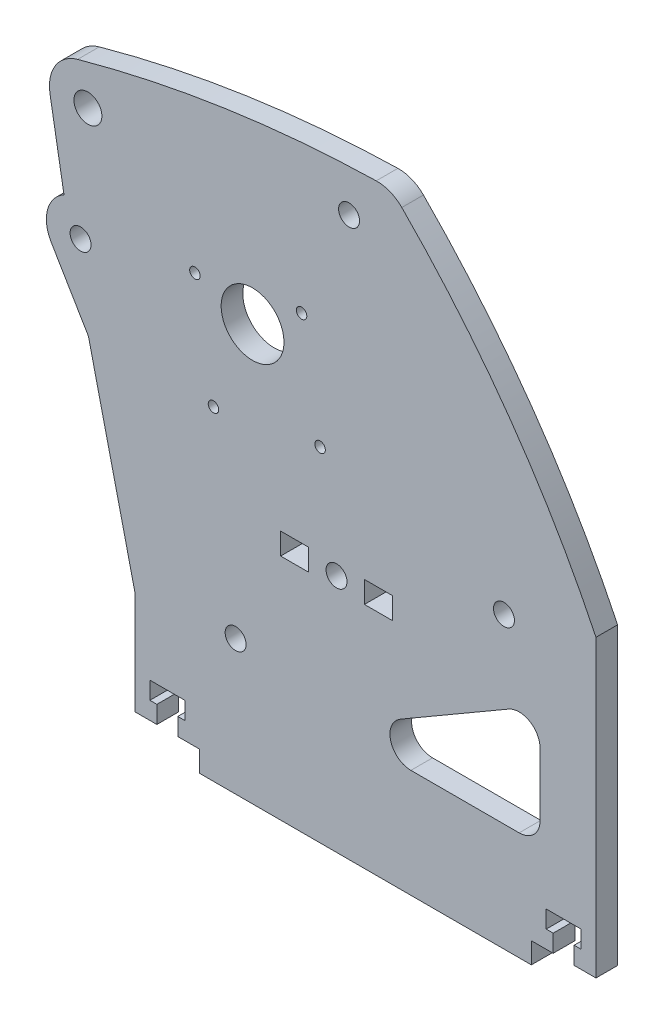
SolidWorks part; units mm, degrees
ref_plane "Front Plane" through (0, 0, 0) normal (0, 0, 1) x (1, 0, 0)
ref_plane "Top Plane" through (0, 0, 0) normal (0, 1, 0) x (1, 0, 0)
ref_plane "Right Plane" through (0, 0, 0) normal (1, 0, 0) x (0, 0, -1)
sketch "Sketch1" plane through (0, 0, 0) normal (0, 0, 1) x (1, 0, 0)
  line L5 (-57.6783, -8.5) -> (-47, -26.5)
  line L7 (-33.65, -83.5) -> (-33.65, -113)
  line L8 (-33.65, -113) -> (-15.15, -113)
  line L12 (82.35, -64) -> (82.35, -82)
  line L13 (76.35, -88) -> (45.35, -88)
  line L14 (42.3372, -76.8113) -> (73.3372, -58.8113)
  line L15 (98.35, -28.5) -> (98.35, -113)
  line L16 (-47, -26.5) -> (-33.65, -83.5)
  line L17 (-58, 28.0717) -> (-54, 5.0717)
  line L18 (-15.15, -113) -> (-15.15, -119)
  line L19 (-15.15, -119) -> (79.85, -119)
  line L20 (79.85, -119) -> (79.85, -113)
  line L21 (79.85, -113) -> (98.35, -113)
  circle A0 centre (-47.15, 30) radius 4
  circle A1 centre (0, 0) radius 18.05 construction
  circle A2 centre (27.65, 40.9) radius 3
  circle A3 centre (-4.85, -80.4) radius 3
  circle A4 centre (-49.25, -3.5) radius 3
  circle A5 centre (72, -36) radius 3
  circle A6 centre (0, 0) radius 9
  arc A7 (-50.0938, 40.6196) -> (-58, 28.0717) centre (-47.15, 30) ccw
  arc A8 (-54, 5.0717) -> (-57.6783, -8.5) centre (-49.25, -3.5) ccw
  arc A10 (98.35, -28.5) -> (42.7481, 50.2939) centre (-163.098, -153.9789) ccw
  arc A11 (42.7481, 50.2939) -> (35.422, 53.2474) centre (35.65, 43.25) ccw
  arc A13 (82.35, -64) -> (73.3372, -58.8113) centre (76.35, -64) ccw
  arc A14 (76.35, -88) -> (82.35, -82) centre (76.35, -82) ccw
  arc A15 (42.3372, -76.8113) -> (45.35, -88) centre (45.35, -82) ccw
  arc A16 (-50.0938, 40.6196) -> (35.422, 53.2474) centre (43.4017, -296.6616) cw
  dimension "D1" = 18
  dimension "D3" = 40.9
  dimension "D4" = 6
  dimension "D5" = 47.15
  dimension "D6" = 30
  dimension "D7" = 8
  dimension "D8" = 72
  dimension "D10" = 49.25
  dimension "D11" = 3.5
  dimension "D12" = 80.4
  dimension "D13" = 4.85
  dimension "D25" = 350
  dimension "D26" = 10
  dimension "D29" = 290
  dimension "D34" = 6
  dimension "D2" = 27.65
  dimension "D9" = 36
  dimension "D14" = 113
  dimension "D15" = 132
  dimension "D16" = 33.65
  dimension "D17" = 83.5
  dimension "D18" = 47
  dimension "D19" = 57
  dimension "D20" = 84.5
  dimension "D21" = 18
  dimension "D22" = 54
  dimension "D23" = 23
  dimension "D24" = 58
  dimension "D27" = 2.35
  dimension "D28" = 8
  dimension "D30" = 31
  dimension "D31" = 18
  dimension "D32" = 16
  dimension "D33" = 25
  dimension "D35" = 95
  dimension "D36" = 6
  dimension "D37" = 18.5
extrude "Boss-Extrude1" add sketch "Sketch1" along normal blind 6.2
sketch "Sketch2" plane through (0, 0, 6.2) normal (0, 0, 1) x (1, 0, 0)
  circle A0 centre (19.3487, -20.7923) radius 1.5 construction
  circle A1 centre (-11.1929, -26.1038) radius 1.5 construction
  circle A2 centre (-16.5044, 4.4377) radius 1.5 construction
  circle A3 centre (14.0371, 9.7493) radius 1.5 construction
  circle A4 centre (19.3487, -20.7923) radius 1.5
  circle A5 centre (-11.1929, -26.1038) radius 1.5
  circle A6 centre (-16.5044, 4.4377) radius 1.5
  circle A7 centre (14.0371, 9.7493) radius 1.5
extrude "Cut-Extrude1" cut sketch "Sketch2" against normal up to next
ref_plane "Plane1" through (32.35, 0, 0) normal (1, 0, 0) x (0, 0, -1)
sketch "Sketch3" plane through (0, 0, 6.2) normal (0, 0, 1) x (1, 0, 0)
  line L0 (-33.65, -113) -> (-15.15, -113) construction
  line L1 (-29.4, -103) -> (-19.4, -103)
  line L2 (-29.4, -103) -> (-29.4, -108)
  line L3 (-29.4, -108) -> (-27.4, -108)
  line L4 (-19.4, -103) -> (-19.4, -108)
  line L10 (-21.4, -108) -> (-19.4, -108)
  line L12 (-27.4, -108) -> (-27.4, -113)
  line L13 (-27.4, -113) -> (-21.4, -113)
  line L14 (-21.4, -108) -> (-21.4, -113)
  line L15 (-33.65, -83.5) -> (-33.65, -113) construction
  line L16 (32.35, -3.3) -> (32.35, 3.3) construction
  line L17 (86.1, -108) -> (86.1, -113)
  line L18 (92.1, -113) -> (86.1, -113)
  line L19 (92.1, -108) -> (92.1, -113)
  line L20 (86.1, -108) -> (84.1, -108)
  line L21 (84.1, -103) -> (84.1, -108)
  line L22 (94.1, -108) -> (92.1, -108)
  line L23 (94.1, -103) -> (94.1, -108)
  line L24 (94.1, -103) -> (84.1, -103)
  point P20 (-24.4, -113)
  point P21 (-24.4, -103)
  dimension "D1" = 10
  dimension "D2" = 5
  dimension "D3" = 5
  dimension "D4" = 6
  dimension "D5" = 6.25
extrude "Cut-Extrude2" cut sketch "Sketch3" against normal up to next
sketch "Sketch5" plane through (0, 0, 6.2) normal (0, 0, 1) x (1, 0, 0)
  line L0 (32.05, -53.5) -> (40.05, -53.5) construction
  line L1 (40.05, -47.3) -> (40.05, -53.5) construction
  line L2 (32.05, -47.3) -> (40.05, -47.3) construction
  line L3 (32.05, -47.3) -> (32.05, -53.5) construction
  line L4 (32.05, -53.5) -> (40.05, -53.5)
  line L5 (40.05, -47.3) -> (40.05, -53.5)
  line L6 (32.05, -47.3) -> (40.05, -47.3)
  line L7 (32.05, -47.3) -> (32.05, -53.5)
  line L8 (8.05, -47.3) -> (16.05, -47.3) construction
  line L9 (8.05, -47.3) -> (8.05, -53.5) construction
  line L10 (8.05, -53.5) -> (16.05, -53.5) construction
  line L11 (16.05, -47.3) -> (16.05, -53.5) construction
  line L12 (16.05, -47.3) -> (16.05, -53.5)
  line L13 (8.05, -53.5) -> (16.05, -53.5)
  line L14 (8.05, -47.3) -> (8.05, -53.5)
  line L15 (8.05, -47.3) -> (16.05, -47.3)
  line L16 (16.05, -50.4) -> (32.05, -50.4) construction
  circle A0 centre (24.05, -50.4) radius 3
  dimension "D1" = 6
extrude "Cut-Extrude3" cut sketch "Sketch5" against normal up to next
